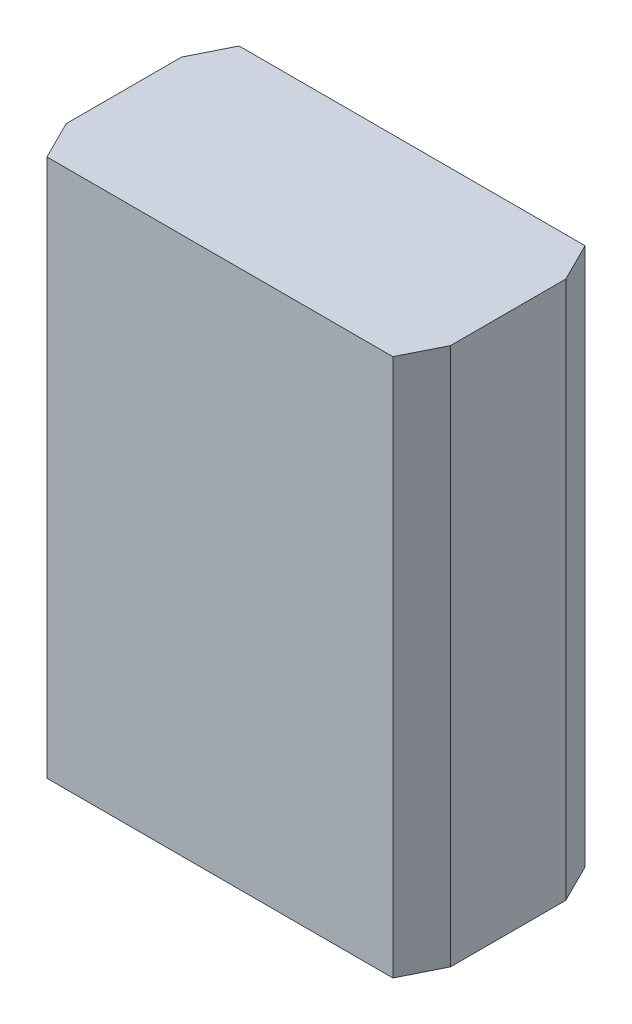
SolidWorks part; units mm, degrees
ref_plane "Front Plane" through (0, 0, 0) normal (0, 0, 1) x (1, 0, 0)
ref_plane "Top Plane" through (0, 0, 0) normal (0, 1, 0) x (1, 0, 0)
ref_plane "Right Plane" through (0, 0, 0) normal (1, 0, 0) x (0, 0, -1)
sketch "Sketch1" plane through (0, 0, 0) normal (0, 1, 0) x (1, 0, 0)
  line L1 (0, 0) -> (2.54, 0)
  line L2 (0, 0) -> (0, 2.54)
  line L3 (0, 2.54) -> (2.54, 2.54)
  line L4 (2.54, 0) -> (2.54, 2.54)
  dimension "D1" = 2.54
  dimension "D2" = 2.54
extrude "Main Body" add sketch "Sketch1" along normal blind 7.112
sketch "Sketch4" plane through (0, 0, 0) normal (0, 1, 0) x (1, 0, 0)
  line L3 (2.54, 2.54) -> (0, 2.54) construction
  line L5 (2.54, 2.54) -> (2.286, 2.54)
  line L6 (2.286, 2.54) -> (2.54, 2.032)
  line L7 (2.54, 0) -> (2.54, 2.54) construction
  line L8 (2.54, 2.032) -> (2.54, 2.54)
  line L9 (2.54, 0) -> (2.286, 0)
  line L10 (0, 0) -> (2.54, 0) construction
  line L11 (2.286, 0) -> (2.54, 0.508)
  line L12 (2.54, 0.508) -> (2.54, 0)
  dimension "D1" = 0.254
  dimension "D2" = 0.508
sketch "Sketch2" plane through (0, 0, 0) normal (0, 1, 0) x (1, 0, 0)
  line L0 (1.27, 2.54) -> (1.27, 1.59) construction
  line L1 (0.95, 0.95) -> (1.59, 0.95)
  line L2 (0.95, 0.95) -> (0.95, 1.59)
  line L3 (0.95, 1.59) -> (1.59, 1.59)
  line L4 (1.59, 0.95) -> (1.59, 1.59)
  line L6 (2.54, 2.54) -> (0, 2.54) construction
  line L8 (1.27, 0.95) -> (1.27, 0) construction
  line L9 (0, 0) -> (2.54, 0) construction
  dimension "D1" = 0.64
ref_plane "Плоскость2" through (0, 0, -1.27) normal (0, 0, 1) x (1, 0, 0)
extrude "Вырез-Вытянуть3" cut sketch "Sketch4" along normal up to surface (7.112 mm away) up to face at (1.27, 7.112, -1.27)
extrude "Вырез-Вытянуть4" cut sketch "Sketch2" along normal blind 6.35
mirror "Зеркальное отражение1" of "Вырез-Вытянуть4", "Вырез-Вытянуть3", "Main Body"
